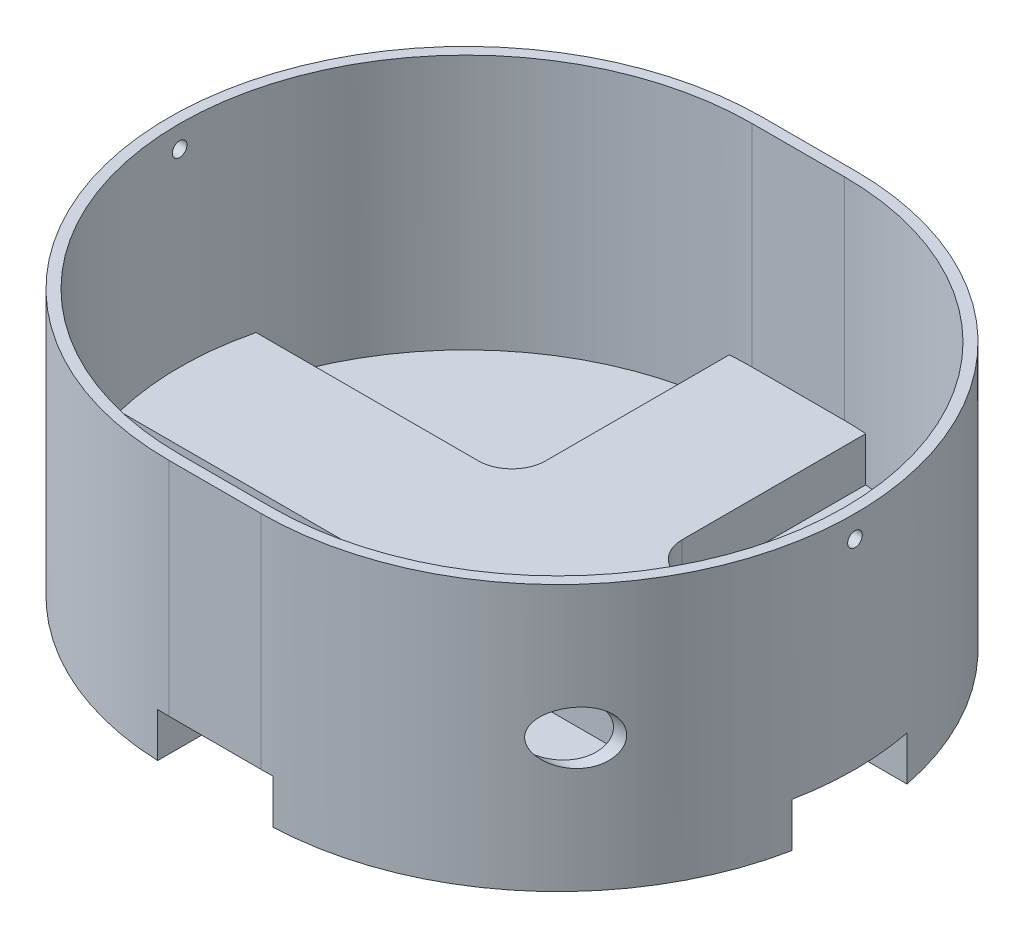
SolidWorks part; units mm, degrees
ref_plane "Front Plane" through (0, 0, 0) normal (0, 0, 1) x (1, 0, 0)
ref_plane "Top Plane" through (0, 0, 0) normal (0, 1, 0) x (1, 0, 0)
ref_plane "Right Plane" through (0, 0, 0) normal (1, 0, 0) x (0, 0, -1)
sketch "Sketch1" plane through (0, 0, 0) normal (0, 1, 0) x (1, 0, 0)
  line L3 (-10.4, 67) -> (10.4, 67)
  line L4 (-10.4, -67) -> (10.4, -67)
  arc A0 (-10.4, -67) -> (-10.4, 67) centre (-10.4, 0) cw
  arc A1 (10.4, -67) -> (10.4, 67) centre (10.4, 0) ccw
  dimension "D3" = 134
extrude "Boss-Extrude1" add sketch "Sketch1" along normal blind 60
sketch "Sketch2" plane through (0, 0, 0) normal (0, -1, 0) x (1, 0, 0)
  line L0 (0, -1026) -> (0, 52.0153) construction
  line L1 (0, 0) -> (50.5754, 0) construction
  line L2 (13, -1026) -> (13, -13) construction
  line L3 (-13, -1026) -> (-13, -13) construction
  line L4 (-91.2517, 13) -> (-13, 13)
  line L5 (-91.2517, 13) -> (-91.2517, -13)
  line L6 (-91.2517, -13) -> (-13, -13)
  line L7 (-13, 91.2517) -> (-13, 13)
  line L8 (13, 91.2517) -> (-13, 91.2517)
  line L9 (13, 13) -> (13, 91.2517)
  line L10 (91.2517, 13) -> (13, 13)
  line L11 (91.2517, -13) -> (91.2517, 13)
  line L12 (-13, -13) -> (-13, -91.2517)
  line L13 (13, -91.2517) -> (13, -13)
  line L17 (13, -13) -> (91.2517, -13)
  line L20 (13, 13) -> (13, 52.0153) construction
  line L21 (-13, 13) -> (-13, 52.0153) construction
  line L22 (13, -1026) -> (13, 52.0153) construction
  line L24 (-13, -1026) -> (-13, 52.0153) construction
  line L26 (-13, -91.2517) -> (13, -91.2517)
  point P31 (0, 0)
  point P40 (0, 0)
  dimension "D1" = 13
  dimension "D3" = 4
  dimension "D2" = 13
extrude "Cut-Extrude1" cut sketch "Sketch2" against normal blind 10
fillet "Fillet1" radius 10 4 edges at (13, 5, 13) (-13, 5, 13) (-13, 5, -13) (13, 5, -13)
shell "Shell1" thickness 2.4
sketch "Sketch3" plane through (0, 0, 0) normal (1, 0, 0) x (0, 0, -1)
  line L1 (67, 60) -> (-67, 60) construction
  circle A0 centre (0, 55) radius 1.65
  dimension "D1" = 3.3
  dimension "D2" = 5
extrude "Cut-Extrude2" cut sketch "Sketch3" against normal through all both and the other way through all
sketch "Sketch4" plane through (0, 0, 0) normal (1, 0, 0) x (0, 0, -1)
  line L0 (0, 0) -> (0, 60) construction
  line L1 (67, 60) -> (-67, 60) construction
  line L2 (0, 30) -> (-67, 30) construction
  line L3 (-67, 60) -> (-67, 10) construction
  circle A0 centre (-45, 30) radius 6
  dimension "D1" = 12
  dimension "D2" = 45
extrude "Cut-Extrude3" cut sketch "Sketch4" along normal through all
